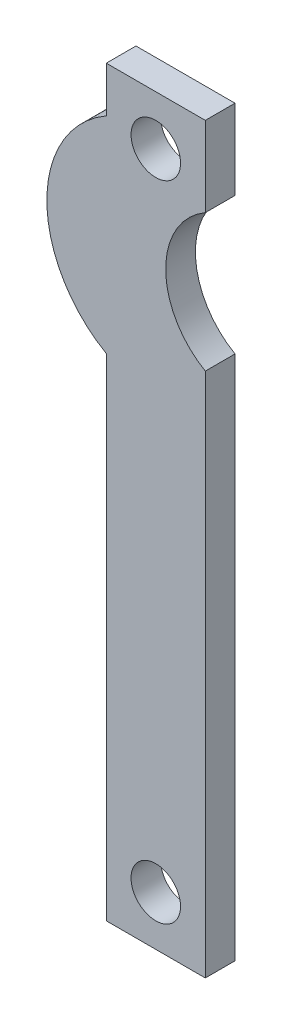
SolidWorks part; units mm, degrees
ref_plane "Piano frontale" through (0, 0, 0) normal (0, 0, 1) x (1, 0, 0)
ref_plane "Piano superiore" through (0, 0, 0) normal (0, 1, 0) x (1, 0, 0)
ref_plane "Piano destro" through (0, 0, 0) normal (1, 0, 0) x (0, 0, -1)
sketch "Schizzo1" plane through (0, 0, 0) normal (0, 0, 1) x (1, 0, 0)
  line L0 (-10, 75) -> (0, 75)
  line L1 (0, 75) -> (0, 66.9282)
  line L2 (-10, 75) -> (-10, 70.3923)
  line L3 (-10, 0) -> (-10, 49.6077)
  line L4 (0, 53.0718) -> (0, 0)
  line L7 (0, 0) -> (-10, 0)
  circle A0 centre (-5, 70) radius 2.5
  circle A1 centre (-5, 5) radius 2.5
  arc A2 (-10, 70.3923) -> (-10, 49.6077) centre (-4, 60) ccw
  arc A3 (0, 66.9282) -> (0, 53.0718) centre (4, 60) ccw
  dimension "D1" = 5
  dimension "D4" = 5
  dimension "D8" = 5
  dimension "D11" = 6
  dimension "D12" = 4
  dimension "D13" = 12
  dimension "D10" = 8
  dimension "D14" = 15
  dimension "D2" = 10
  dimension "D5" = 5
  dimension "D6" = 5
  dimension "D7" = 5
  dimension "D9" = 75
  dimension "D15" = 10
extrude "Estrusione-Estrusione3" add sketch "Schizzo1" along normal blind 3
